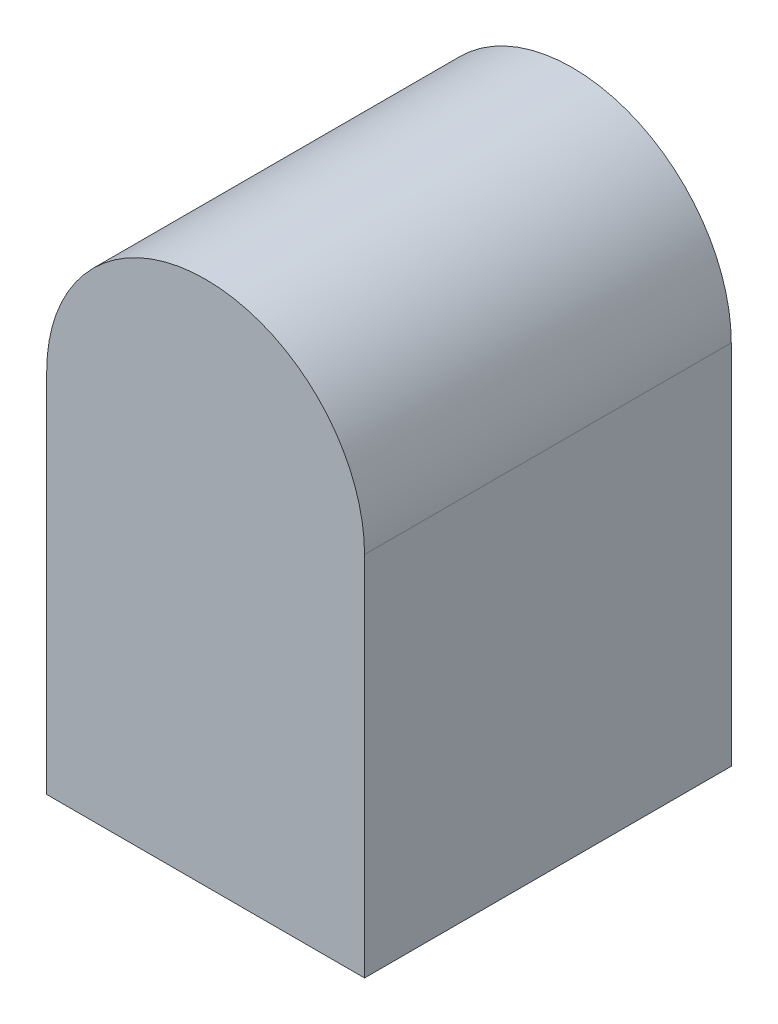
SolidWorks part; units mm, degrees
ref_plane "Front Plane" through (0, 0, 0) normal (0, 0, 1) x (1, 0, 0)
ref_plane "Top Plane" through (0, 0, 0) normal (0, 1, 0) x (1, 0, 0)
ref_plane "Right Plane" through (0, 0, 0) normal (1, 0, 0) x (0, 0, -1)
sketch "Sketch1" plane through (0, 0, 0) normal (0, 0, 1) x (1, 0, 0)
  line L2 (0, 0) -> (0, -30)
  line L3 (0, -30) -> (26, -30)
  line L4 (26, 0) -> (26, -30)
  arc A0 (26, 0) -> (0, 0) centre (13, 0) ccw
  dimension "D1" = 30
  dimension "D2" = 26
extrude "Boss-Extrude1" add sketch "Sketch1" along normal blind 30
sketch "Sketch2" plane through (0, 0, 0) normal (0, 0, -1) x (-1, 0, 0)
  line L0 (0, -30) -> (-26, -30) construction
  line L1 (-26, -30) -> (-26, 0) construction
  circle A0 centre (-13, -10) radius 2.5
  point P4 (0, 0)
  dimension "D1" = 5
  dimension "D2" = 20
  dimension "D3" = 13
extrude "Boss-Extrude2" add sketch "Sketch2" along normal blind 10
